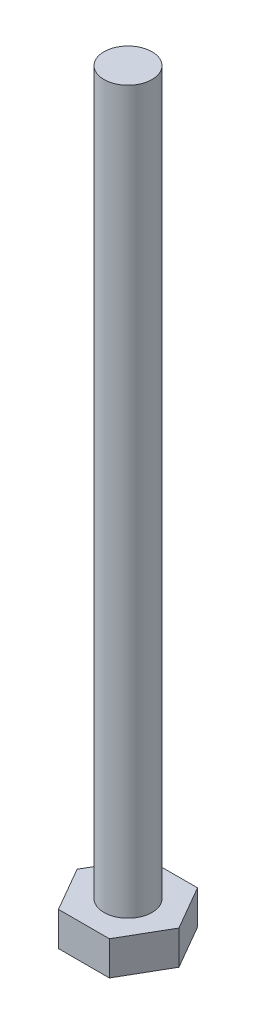
SolidWorks part; units mm, degrees
ref_plane "前视基准面" through (0, 0, 0) normal (0, 0, 1) x (1, 0, 0)
ref_plane "上视基准面" through (0, 0, 0) normal (0, 1, 0) x (1, 0, 0)
ref_plane "右视基准面" through (0, 0, 0) normal (1, 0, 0) x (0, 0, -1)
sketch "草图1" plane through (0, 0, 0) normal (0, 1, 0) x (1, 0, 0)
  circle A0 centre (0, 0) radius 1.5
  dimension "D1" = 3
extrude "凸台-拉伸1" add sketch "草图1" along normal blind 45
sketch "草图3" plane through (0, 0, 0) normal (0, -1, 0) x (1, 0, 0)
  line L1 (3.1754, 0) -> (1.5877, 2.75)
  line L2 (1.5877, 2.75) -> (-1.5877, 2.75)
  line L3 (-1.5877, 2.75) -> (-3.1754, 0)
  line L4 (-3.1754, 0) -> (-1.5877, -2.75)
  line L5 (-1.5877, -2.75) -> (1.5877, -2.75)
  line L6 (1.5877, -2.75) -> (3.1754, 0)
  circle A0 centre (0, 0) radius 2.75 construction
  dimension "D1" = 5.5
extrude "凸台-拉伸2" add sketch "草图3" along normal blind 2.12 contours L5 L6 L1 L2 L3 L4
